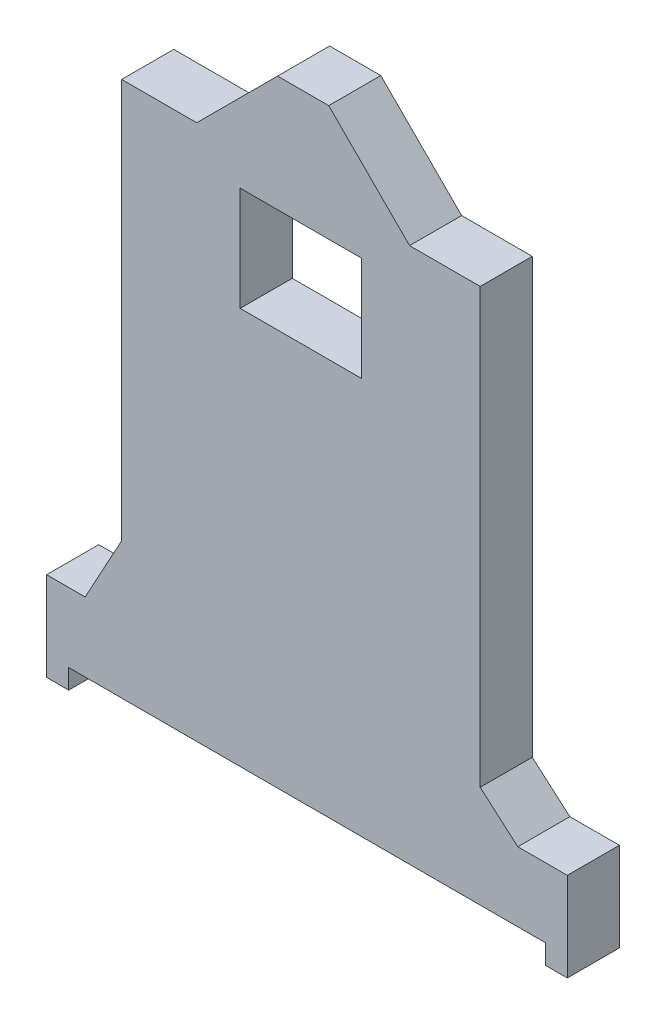
SolidWorks part; units mm, degrees
ref_plane "Front Plane" through (0, 0, 0) normal (0, 0, 1) x (1, 0, 0)
ref_plane "Top Plane" through (0, 0, 0) normal (0, 1, 0) x (1, 0, 0)
ref_plane "Right Plane" through (0, 0, 0) normal (1, 0, 0) x (0, 0, -1)
sketch "Sketch1" plane through (0, 0, 0) normal (0, 0, 1) x (1, 0, 0)
  line L0 (32.3, 0) -> (32.3, 28.6263)
  line L1 (0, 0) -> (32.3, 0)
  line L2 (0, 0) -> (0, 130.1412)
  line L3 (109.8465, 812.8) -> (634.5183, 812.8)
  line L4 (762, 0) -> (762, 130.1412)
  line L5 (32.3, 28.6263) -> (729.742, 28.6263)
  line L6 (729.742, 28.6263) -> (729.742, 0)
  line L7 (0, 130.1412) -> (56.3706, 130.1412)
  line L8 (56.3706, 130.1412) -> (219.6316, 429.453)
  line L9 (219.6316, 429.453) -> (345.217, 429.453)
  line L10 (345.217, 429.453) -> (689.5302, 130.1412)
  line L11 (109.8465, 228.1804) -> (109.8465, 812.8)
  line L12 (634.5183, 177.9631) -> (634.5183, 812.8)
  line L13 (219.6316, 812.8) -> (337.9407, 931.1091)
  line L14 (337.9407, 931.1091) -> (412.8536, 931.1091)
  line L15 (412.8536, 931.1091) -> (531.1626, 812.8)
  line L16 (729.742, 0) -> (762, 0)
  line L17 (689.5302, 130.1412) -> (762, 130.1412)
  line L18 (372.1824, 406.012) -> (372.1824, 812.8) construction
  line L19 (109.8465, 685.5312) -> (634.5183, 685.5312) construction
  line L21 (283.2824, 761.7312) -> (461.0824, 761.7312)
  line L22 (283.2824, 761.7312) -> (283.2824, 609.3312)
  line L23 (283.2824, 609.3312) -> (461.0824, 609.3312)
  line L24 (461.0824, 761.7312) -> (461.0824, 609.3312)
  point P29 (372.1824, 761.7312)
  point P30 (461.0824, 685.5312)
  dimension "D1" = 762
  dimension "D2" = 177.8
  dimension "D3" = 45
  dimension "D4" = 45
  dimension "D5" = 32.3
  dimension "D6" = 32.258
  dimension "D7" = 152.4
extrude "Boss-Extrude1" add sketch "Sketch1" along normal blind 76.2 contours L10 L12 L3 L11 L8 L9 | L15 L14 L13 L3
